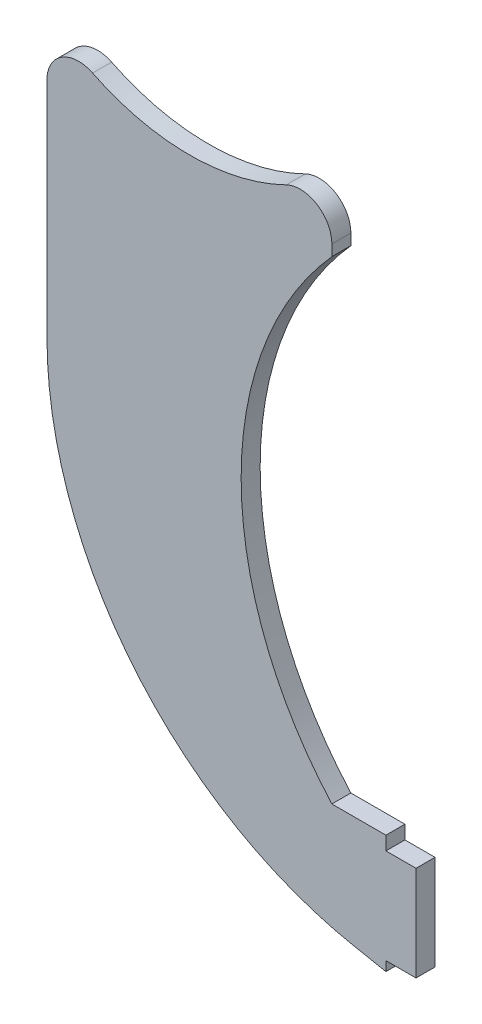
SolidWorks part; units mm, degrees
ref_plane "Front Plane" through (0, 0, 0) normal (0, 0, 1) x (1, 0, 0)
ref_plane "Top Plane" through (0, 0, 0) normal (0, 1, 0) x (1, 0, 0)
ref_plane "Right Plane" through (0, 0, 0) normal (1, 0, 0) x (0, 0, -1)
sketch "Sketch1" plane through (0, 0, 0) normal (0, 0, 1) x (1, 0, 0)
  line L0 (-79.1232, -194.7897) -> (-79.1232, -164.7897)
  line L1 (-79.1232, -164.7897) -> (-88.6232, -164.7897)
  line L2 (-88.6232, -164.7897) -> (-88.6232, -160.487)
  line L4 (-88.6232, -160.487) -> (-105.6868, -160.487)
  line L9 (-105.6868, -10.8428) -> (-105.6868, 11.053)
  line L11 (-195.6283, 11.053) -> (-195.6283, -78.076)
  line L12 (-98.4522, -195.8855) -> (-88.6232, -197.7897)
  line L13 (-88.6232, -197.7897) -> (-88.6232, -194.7897)
  line L14 (-88.6232, -194.7897) -> (-79.1232, -194.7897)
  arc A1 (-105.6868, -160.487) -> (-105.6868, -10.8428) centre (-22.2755, -85.6649) cw
  arc A3 (-195.6283, 11.053) -> (-105.6868, 11.053) centre (-150.6576, 63.8133) ccw
  arc A4 (-195.6283, -78.076) -> (-98.4522, -195.8855) centre (-75.6283, -78.076) ccw
  point P11 (0, 0)
  dimension "D1" = 120
extrude "Boss-Extrude1" add sketch "Sketch1" along normal blind 6
fillet "Fillet1" radius 10 1 edges at (-195.6283, 11.053, 3)
fillet "Fillet2" radius 10 1 edges at (-105.6868, 11.053, 3)
